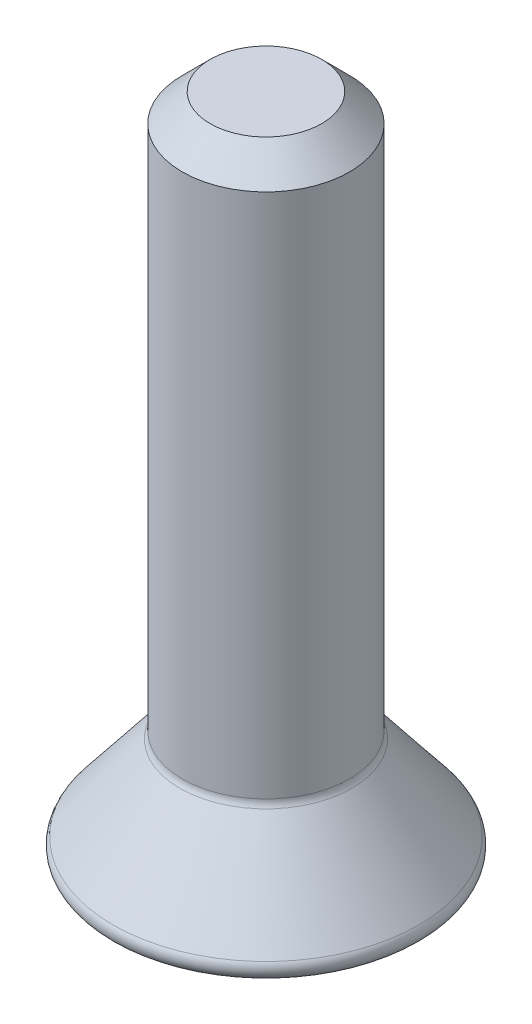
SolidWorks part; units mm, degrees
ref_plane "前视基准面" through (0, 0, 0) normal (0, 0, 1) x (1, 0, 0)
ref_plane "上视基准面" through (0, 0, 0) normal (0, 1, 0) x (1, 0, 0)
ref_plane "右视基准面" through (0, 0, 0) normal (1, 0, 0) x (0, 0, -1)
sketch "草图1" plane through (0, 0, 0) normal (0, 0, 1) x (1, 0, 0)
  line L0 (0, 3.3103) -> (0, -3.8641) construction
  line L1 (0, 1.9) -> (1.5, 1.9)
  line L2 (1.5, 1.9) -> (3, 0)
  line L3 (3, 0) -> (0, 0)
  line L4 (0, 1.9) -> (0, 0)
  dimension "D1" = 1.5
  dimension "D2" = 3
  dimension "D3" = 1.9
revolve "旋转2" add sketch "草图1" angle 360 about L0
sketch "草图2" plane through (0, 1.9, 0) normal (0, 1, 0) x (1, 0, 0)
  circle A0 centre (0, 0) radius 1.5
extrude "凸台-拉伸1" add sketch "草图2" along normal blind 10
sketch "草图3" plane through (0, 0, 0) normal (0, -1, 0) x (1, 0, 0)
  line L1 (0, 1.1547) -> (-1, 0.5774)
  line L2 (-1, 0.5774) -> (-1, -0.5774)
  line L3 (-1, -0.5774) -> (0, -1.1547)
  line L4 (0, -1.1547) -> (1, -0.5774)
  line L5 (1, -0.5774) -> (1, 0.5774)
  line L6 (1, 0.5774) -> (0, 1.1547)
  circle A1 centre (0, 0) radius 1 construction
  dimension "D1" = 2
extrude "切除-拉伸1" cut sketch "草图3" against normal blind 1
chamfer "倒角1" distance 0.5 angle 45 1 edges at (0, 11.9, 1.5)
fillet "圆角1" radius 0.2 2 edges at (0, 1.9, 1.5) (0, 0, 3)
